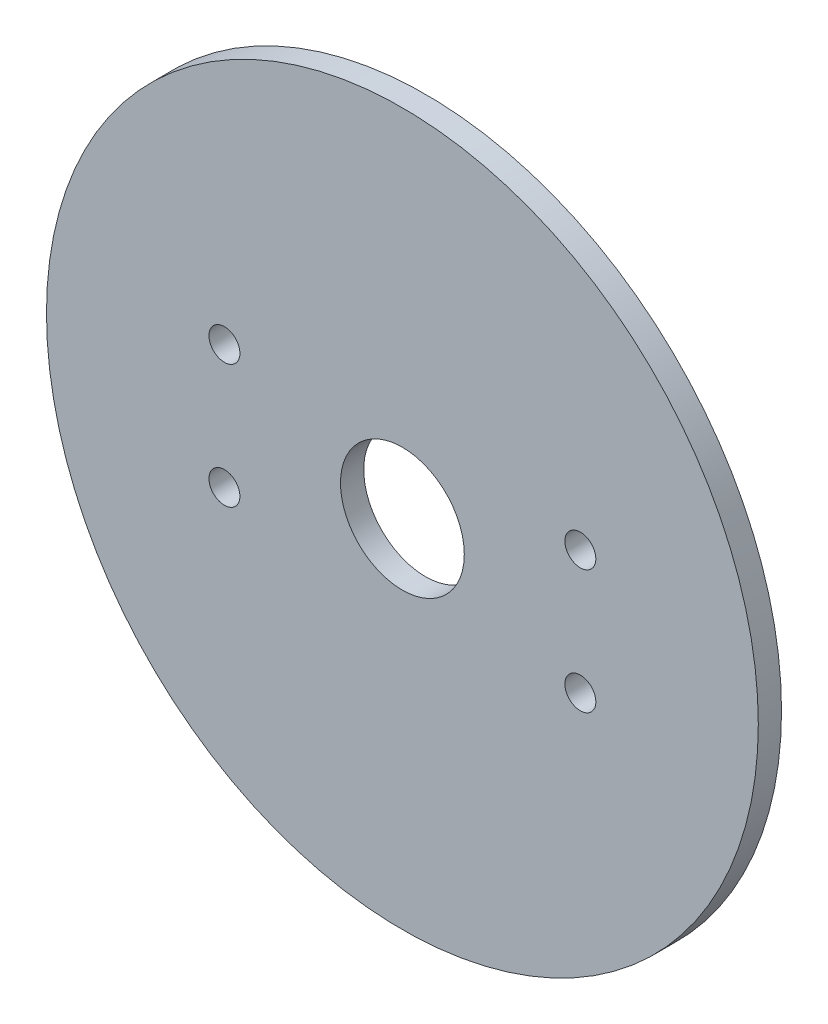
SolidWorks part; units mm, degrees
ref_plane "정면" through (0, 0, 0) normal (0, 0, 1) x (1, 0, 0)
ref_plane "윗면" through (0, 0, 0) normal (0, 1, 0) x (1, 0, 0)
ref_plane "우측면" through (0, 0, 0) normal (1, 0, 0) x (0, 0, -1)
sketch "스케치1" plane through (0, 0, 0) normal (0, 0, 1) x (1, 0, 0)
  circle A0 centre (0, 0) radius 46
extrude "보스-돌출1" add sketch "스케치1" along normal blind 3
sketch "스케치2" plane through (0, 0, 3) normal (0, 0, 1) x (1, 0, 0)
  circle A0 centre (0, 0) radius 8
extrude "컷-돌출1" cut sketch "스케치2" against normal blind 3
sketch "스케치3" plane through (0, 0, 3) normal (0, 0, 1) x (1, 0, 0)
  line L0 (-56.0789, 0) -> (55.5902, 0) construction
  line L1 (0, 49.5425) -> (0, -49.6646) construction
  line L2 (-56.0789, -15) -> (55.5902, -15)
  line L3 (-56.0789, 15) -> (55.5902, 15)
  line L4 (-30, 49.5425) -> (-30, -49.6646)
  line L5 (30, 49.5425) -> (30, -49.6646)
  circle A0 centre (-23, 8) radius 2
  circle A1 centre (-23, -8) radius 2
  circle A2 centre (23, -8) radius 2
  circle A3 centre (23, 8) radius 2
  dimension "D5" = 4
  dimension "D6" = 7
  dimension "D7" = 7
  dimension "D1" = 15
  dimension "D2" = 15
  dimension "D3" = 30
  dimension "D4" = 30
extrude "컷-돌출2" cut sketch "스케치3" against normal blind 3 contours A0 | A1 | A2 | A3
